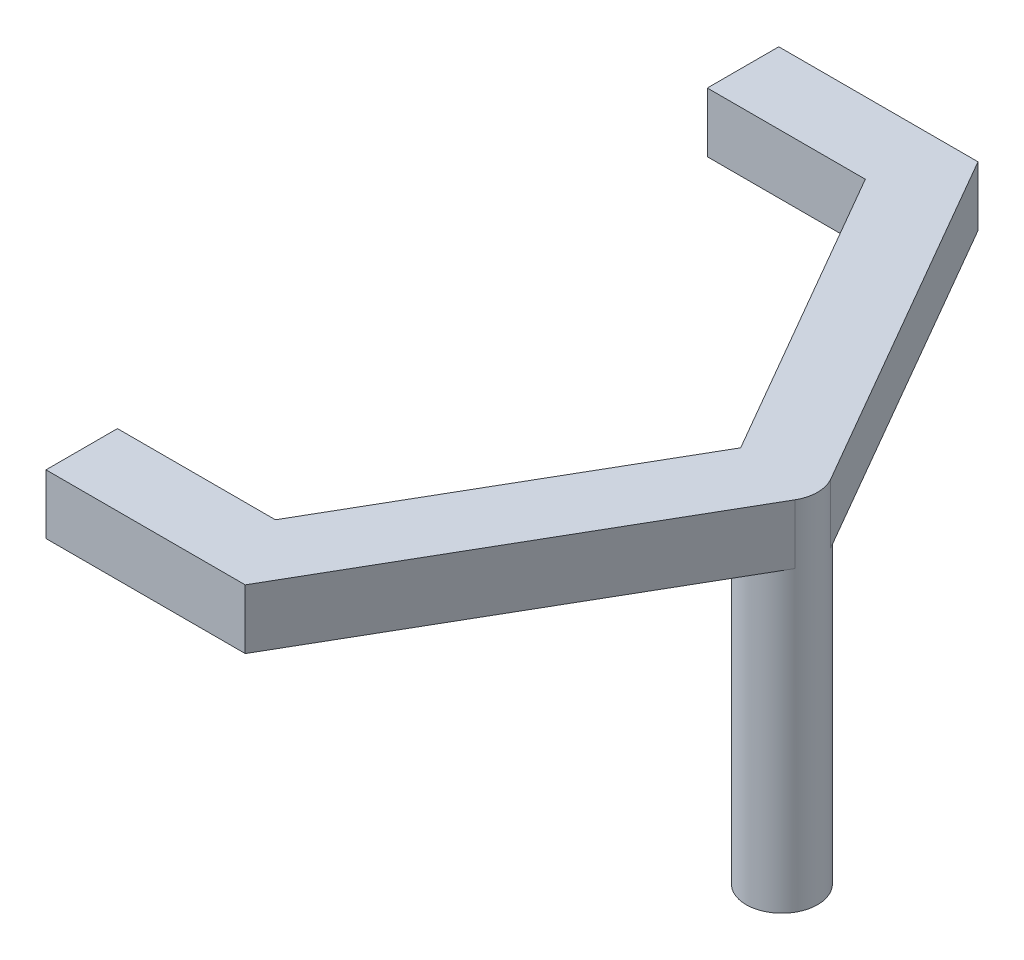
SolidWorks part; units mm, degrees
material "Copper"
ref_plane "Front Plane" through (0, 0, 0) normal (0, 0, 1) x (1, 0, 0)
ref_plane "Top Plane" through (0, 0, 0) normal (0, 1, 0) x (1, 0, 0)
ref_plane "Right Plane" through (0, 0, 0) normal (1, 0, 0) x (0, 0, -1)
sketch "Sketch1" plane through (0, 0, 0) normal (0, 1, 0) x (1, 0, 0)
  circle A0 centre (0, 0) radius 3
  dimension "D1" = 6
extrude "Steering Column" add sketch "Sketch1" along normal blind 30
sketch "Sketch2" plane through (0, 30, 0) normal (0, 1, 0) x (1, 0, 0)
  line L0 (0, 0) -> (-16.033, 27.77) construction
  line L1 (-16.033, 27.77) -> (-31.033, 27.77) construction
  line L2 (-16.5, 0) -> (16.5, 0) construction
  line L3 (2.5981, 1.5) -> (-14.301, 30.77)
  line L4 (-14.301, 30.77) -> (-31.033, 30.77)
  line L5 (-2.5981, -1.5) -> (-17.7651, 24.77)
  line L6 (-17.7651, 24.77) -> (-31.033, 24.77)
  line L7 (-31.033, 30.77) -> (-31.033, 24.77)
  line L8 (-2.5981, -1.5) -> (2.5981, 1.5)
  dimension "D2" = 60
  dimension "D3" = 15
  dimension "D5" = 3
  dimension "D1" = 27.77
  dimension "D4" = 3
extrude "Left Handle Bar" add sketch "Sketch2" against normal blind 5
mirror "Mirror1" about plane through (0, 0, 0) normal (0, 0, 1) of "Left Handle Bar"
equation "\"D5@Sketch2\"=\"D4@Sketch2\""
